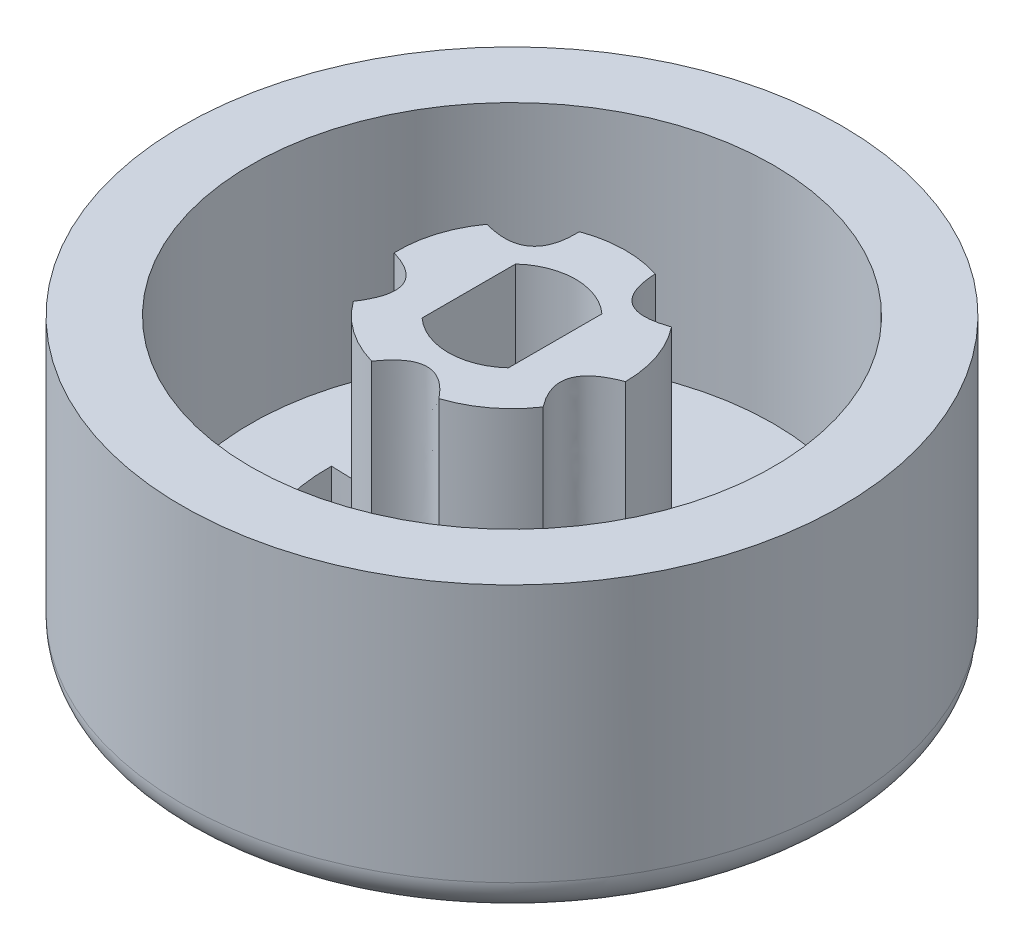
SolidWorks part; units mm, degrees
ref_plane "Alzado" through (0, 0, 0) normal (0, 0, 1) x (1, 0, 0)
ref_plane "Planta" through (0, 0, 0) normal (0, 1, 0) x (1, 0, 0)
ref_plane "Vista lateral" through (0, 0, 0) normal (1, 0, 0) x (0, 0, -1)
sketch "Croquis1" plane through (0, 0, 0) normal (0, 1, 0) x (1, 0, 0)
  circle A0 centre (0, 0) radius 14.5
  dimension "D1" = 29
extrude "Saliente-Extruir1" add sketch "Croquis1" along normal blind 12.85
shell "Vaciado1" thickness 3
fillet "Redondeo1" radius 1.5 1 edges at (0, 0, 14.5)
sketch "Croquis2" plane through (0, 0, 0) normal (0, -1, 0) x (1, 0, 0)
  circle A0 centre (0, 0) radius 8.1
  dimension "D1" = 16.2
extrude "Saliente-Extruir2" add sketch "Croquis2" along normal blind 4
fillet "Redondeo2" radius 1.5 1 edges at (0, -4, -8.1)
sketch "Croquis3" plane through (0, -4, 0) normal (0, -1, 0) x (1, 0, 0)
  circle A0 centre (0, 0) radius 1.55
  dimension "D1" = 3.1
sketch "Croquis5" plane through (0, 3, 0) normal (0, 1, 0) x (1, 0, 0)
  circle A0 centre (0, 0) radius 5
  dimension "D1" = 10
extrude "Saliente-Extruir3" add sketch "Croquis5" along normal up to surface (9.85 mm away) up to face at (0, 12.85, 11.5)
sketch "Croquis6" plane through (0, 12.85, 0) normal (0, 1, 0) x (1, 0, 0)
  line L2 (-1.9, 2.0567) -> (-1.9, -2.0567)
  line L4 (1.9, 2.0567) -> (1.9, -2.0567)
  circle A0 centre (0, 0) radius 2.8
  dimension "D1" = 5.6
extrude "Cortar-Extruir3" cut sketch "Croquis6" against normal blind 7 contours L4 A0 L2
hole_wizard "Refrentado para tornillo con cabeza troncocónica de M2.51" positions "Croquis3D3" profile "Croquis10" counterbore size "M2.5" standard "Ansi Metric" end condition through all
sketch3d "Croquis3D3"
  point P0 (0, 0, 0)
  point P4 (0, -4, 0)
sketch "Croquis10" plane through (0, -4, 0) normal (1, 0, 0) x (0, 0, -1)
  line L0 (0, 0) -> (0, 16.85)
  line L1 (0, 16.85) -> (1.45, 16.85)
  line L3 (1.45, 16.85) -> (1.45, 2.1)
  line L4 (1.45, 2.1) -> (3, 2.1)
  line L5 (3, 2.1) -> (3, 0)
  line L7 (3, 0) -> (0, 0)
  line L11 (0, -6.35) -> (0, 107.95) construction
  dimension "Diámetro de taladro hasta el siguiente" = 2.9
  dimension "Profundidad de taladro hasta el siguiente" = 16.85
  dimension "Diámetro de refrentado" = 6
  dimension "Profundidad de refrentado" = 2.1
sketch "Croquis4" plane through (0, -4, 0) normal (0, -1, 0) x (1, 0, 0)
  circle A0 centre (0, 0) radius 8.1
  spline S0 degree 2 poles (-2.6489, 7.6546) (-0.1271, 0.0255) (3.0481, 7.5046) knots 0 0 0 1 1 1
  spline S1 degree 2 poles (6.4614, 4.8847) (-0.015, 0.1288) (8.0792, -0.5799) knots 0 0 0 1 1 1
  spline S2 degree 2 poles (6.6423, -4.6357) (0.1178, 0.0541) (1.9451, -7.863) knots 0 0 0 1 1 1
  spline S3 degree 2 poles (-2.3562, -7.7497) (0.0879, -0.0953) (-6.8771, -4.2797) knots 0 0 0 1 1 1
  spline S4 degree 2 poles (-8.0985, -0.1539) (-0.0635, -0.113) (-6.1954, 5.218) knots 0 0 0 1 1 1
  circle M3 centre (0, 0) radius 6.6
extrude "Cortar-Extruir2" cut sketch "Croquis4" against normal blind 37 contours S4 M3 | A0 S4 M3 | A0 S3 M3 | S3 M3 | A0 S2 M3 | S2 M3 | S1 M3 | A0 S1 M3 | S0 M3 | A0 S0 M3
sketch "Croquis11" plane through (0, -1.9, 0) normal (0, -1, 0) x (-1, 0, 0)
  circle A0 centre (0, 0) radius 2.59
  dimension "D1" = 5.18
sketch "Croquis12" plane through (0, -1.9, 0) normal (0, -1, 0) x (1, 0, 0)
  circle A0 centre (0, 0) radius 2.9756
extrude "Cortar-Extruir4" cut sketch "Croquis12" against normal blind 5
